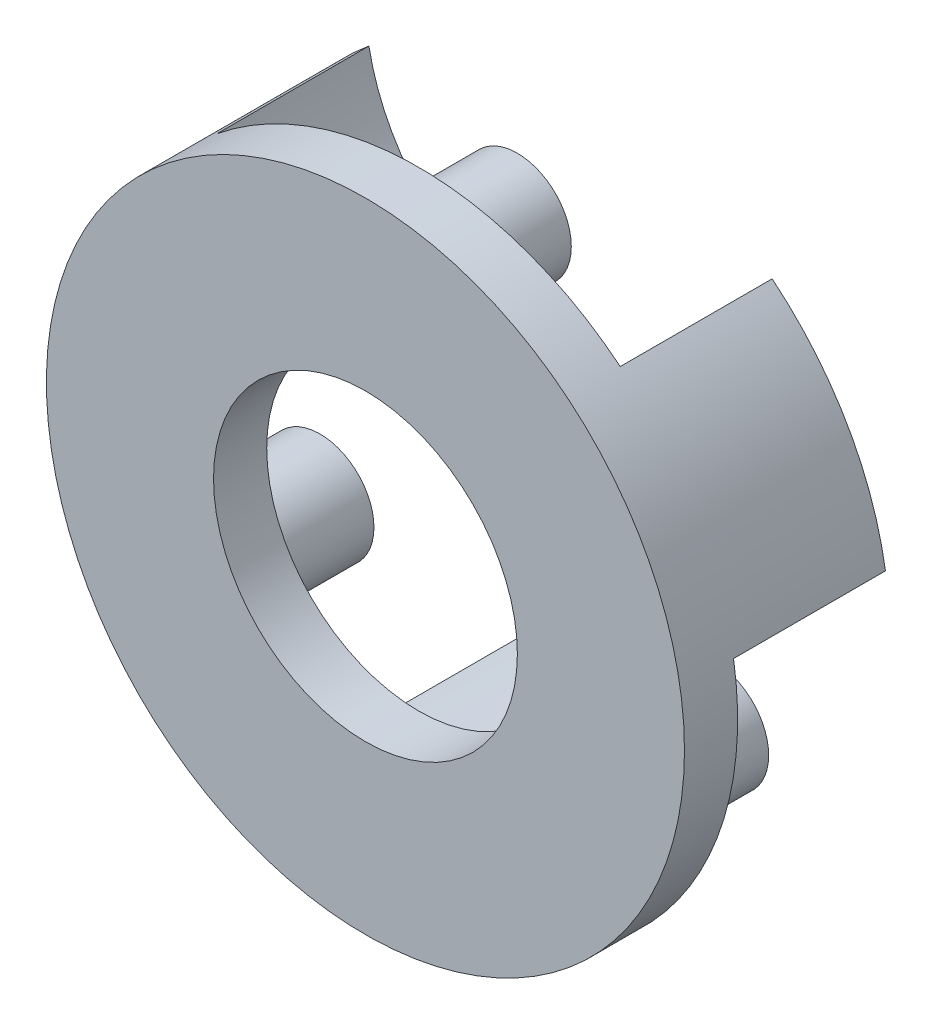
SolidWorks part; units mm, degrees
ref_plane "Front Plane" through (0, 0, 0) normal (0, 0, 1) x (1, 0, 0)
ref_plane "Top Plane" through (0, 0, 0) normal (0, 1, 0) x (1, 0, 0)
ref_plane "Right Plane" through (0, 0, 0) normal (1, 0, 0) x (0, 0, -1)
sketch "Sketch1" plane through (0, 0, 0) normal (0, 0, 1) x (1, 0, 0)
  circle A0 centre (0, 0) radius 21
  dimension "D1" = 42
extrude "Boss-Extrude1" add sketch "Sketch1" along normal blind 3.5 contours A0
sketch "Sketch3" plane through (0, 0, 0) normal (0, 0, -1) x (-1, 0, 0)
  line L0 (0, 7.5) -> (0, 18.75) construction
  arc A4 (-7.459, -19.6307) -> (-3.0219, -12.1292) centre (-16.238, -9.375) ccw
  arc A5 (-13.2712, 16.275) -> (-8.9933, 8.6817) centre (0, 18.75) ccw
  arc A6 (20.7302, 3.3557) -> (12.0152, 3.4476) centre (16.238, -9.375) ccw
  circle A7 centre (0, 0) radius 12.5
  arc A9 (8.9933, 8.6817) -> (13.2712, 16.275) centre (0, 18.75) ccw
  arc A10 (-12.0152, 3.4476) -> (-20.7302, 3.3557) centre (-16.238, -9.375) ccw
  arc A11 (-13.2712, 16.275) -> (-20.7302, 3.3557) centre (0, 0) ccw
  arc A12 (-7.459, -19.6307) -> (7.459, -19.6307) centre (0, 0) ccw
  arc A13 (20.7302, 3.3557) -> (13.2712, 16.275) centre (0, 0) ccw
  arc A14 (3.0219, -12.1292) -> (7.459, -19.6307) centre (16.238, -9.375) ccw
  point P13 (0, 0)
  point P19 (0, 0)
  dimension "D1" = 42
  dimension "D2" = 11.25
  dimension "D5" = 27
  dimension "D7" = 25
  dimension "D6" = 3
sketch "Sketch4" plane through (0, 0, 0) normal (0, 0, -1) x (-1, 0, 0)
  circle A0 centre (0, 0) radius 10
  dimension "D1" = 20
extrude "Cut-Extrude1" cut sketch "Sketch4" against normal blind 8.2
sketch "Sketch11" plane through (0, 0, 0) normal (0, 0, -1) x (-1, 0, 0)
  line L0 (0, 0) -> (0, 15) construction
  line L1 (0, 7.5) -> (0, 18.75) construction
  circle A0 centre (0, 15) radius 1.5
  circle A1 centre (12.9904, -7.5) radius 1.5
  circle A2 centre (-12.9904, -7.5) radius 1.5
  point P12 (0, 0)
  dimension "D2" = 3
  dimension "D3" = 3
  dimension "D1" = 15
extrude "Cut-Extrude2" cut sketch "Sketch11" against normal blind 10
extrude "Boss-Extrude2" add sketch "Sketch3" along normal blind 10 contours A10 A7 A5 L0 | A9 A7 A6 L0 | A14 A7 A4 L0
sketch "Sketch14" plane through (0, 0, -10) normal (0, 0, -1) x (-1, 0, 0)
  line L0 (18.1865, 10.5) -> (0, 0) construction
  line L1 (0, 0) -> (13.8564, 8) construction
  arc A0 (20.7302, 3.3557) -> (13.2712, 16.275) centre (0, 0) ccw construction
  circle A1 centre (13.8564, 8) radius 1.5
  circle A2 centre (0, -16) radius 1.5
  circle A3 centre (-13.8564, 8) radius 1.5
  point P14 (0, 0)
  dimension "D2" = 3
  dimension "D1" = 16
  dimension "D3" = 3
extrude "Cut-Extrude3" cut sketch "Sketch14" against normal blind 5
sketch "Sketch16" plane through (0, 0, 3.5) normal (0, 0, 1) x (1, 0, 0)
  circle A0 centre (0, 15) radius 3.55
  circle A1 centre (12.9904, -7.5) radius 3.55
  circle A2 centre (-12.9904, -7.5) radius 3.55
  point P9 (0, 0)
  dimension "D1" = 7.1
  dimension "D2" = 3
extrude "Boss-Extrude3" add sketch "Sketch16" against normal blind 10
